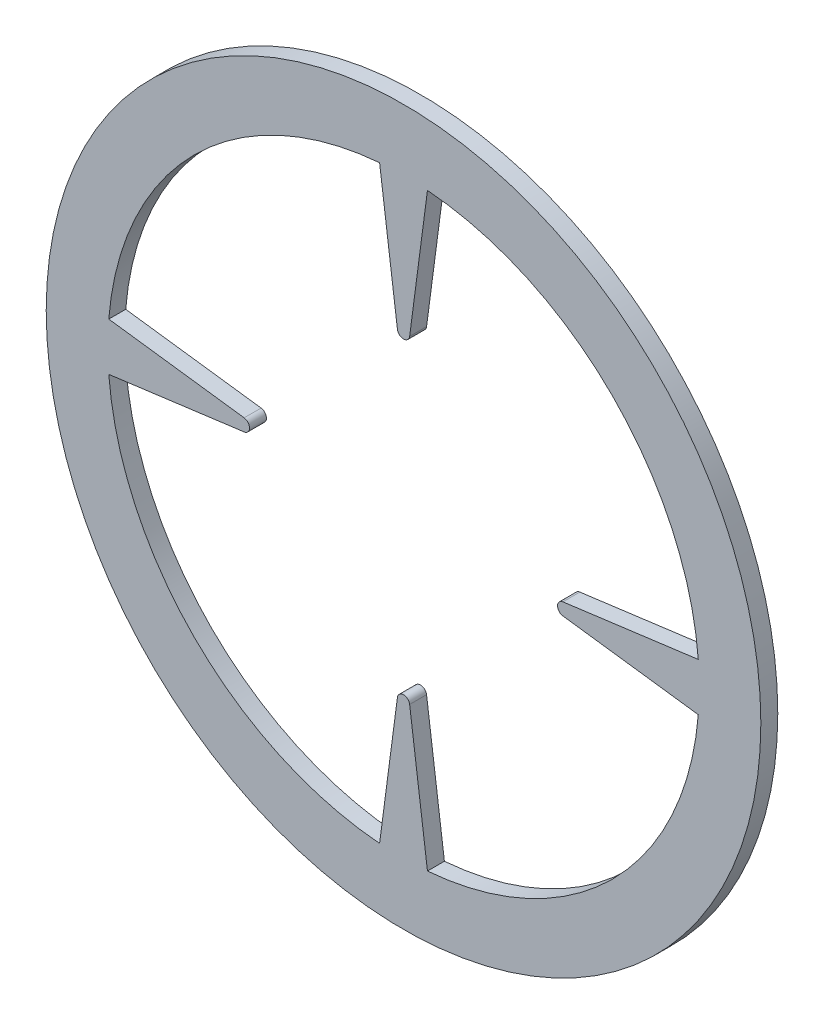
SolidWorks part; units mm, degrees
ref_plane "前基準面" through (0, 0, 0) normal (0, 0, 1) x (1, 0, 0)
ref_plane "上基準面" through (0, 0, 0) normal (0, 1, 0) x (1, 0, 0)
ref_plane "右基準面" through (0, 0, 0) normal (1, 0, 0) x (0, 0, -1)
sketch "草圖1" plane through (0, 0, 0) normal (0, 0, 1) x (1, 0, 0)
  circle A0 centre (0, 0) radius 1.16
  circle A1 centre (0, 0) radius 0.96
  dimension "D1" = 0.2
extrude "填料-伸長1" add sketch "草圖1" along normal blind 0.055
sketch "草圖2" plane through (0, 0, 0.055) normal (0, 0, 1) x (1, 0, 0)
  line L0 (0, 0) -> (0, 1.565) construction
  line L1 (0, 0) -> (-1.8584, 0) construction
  line L12 (-0.0198, 0.5174) -> (-0.0777, 0.9569)
  line L13 (0.0198, 0.5174) -> (0.0777, 0.9569)
  line L15 (0.5174, -0.0198) -> (0.9569, -0.0777)
  line L16 (0.5174, 0.0198) -> (0.9569, 0.0777)
  line L17 (-0.0198, -0.5174) -> (-0.0777, -0.9569)
  line L18 (0.0198, -0.5174) -> (0.0777, -0.9569)
  line L19 (-0.5174, 0.0198) -> (-0.9569, 0.0777)
  line L20 (-0.5174, -0.0198) -> (-0.9569, -0.0777)
  circle A0 centre (0, 0) radius 0.5
  circle A18 centre (0, 0.52) radius 0.02
  arc A19 (0.0777, 0.9569) -> (-0.0777, 0.9569) centre (0, 0) ccw
  circle A20 centre (0, 0) radius 0.96 construction
  arc A21 (0.9569, -0.0777) -> (0.9569, 0.0777) centre (0, 0) ccw
  circle A22 centre (0.52, 0) radius 0.02
  arc A23 (-0.0777, -0.9569) -> (0.0777, -0.9569) centre (0, 0) ccw
  circle A24 centre (0, -0.52) radius 0.02
  arc A25 (-0.9569, 0.0777) -> (-0.9569, -0.0777) centre (0, 0) ccw
  circle A26 centre (-0.52, 0) radius 0.02
  point P17 (0, 0.5)
  point P23 (0, 0)
  point P34 (0, 0)
  point P41 (0, 0)
  point P42 (0, 0)
  circle M4 centre (0, 0) radius 0.96
  dimension "D1" = 7.5
  dimension "D3" = 4
extrude "填料-伸長2" add sketch "草圖2" against normal blind 0.055 contours A18 L13 L12 M4 | A22 L15 L16 M4 | A24 L17 L18 M4 | A26 L19 L20 M4 | A18 | A22 | A24 | A26
